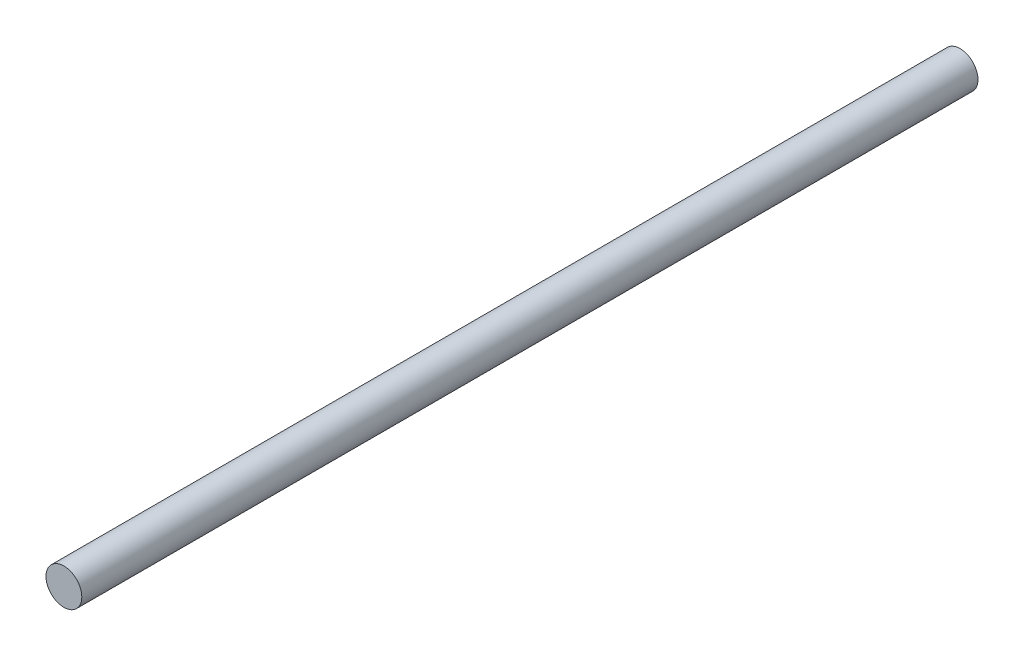
SolidWorks part; units mm, degrees
ref_plane "前视基准面" through (0, 0, 0) normal (0, 0, 1) x (1, 0, 0)
ref_plane "上视基准面" through (0, 0, 0) normal (0, 1, 0) x (1, 0, 0)
ref_plane "右视基准面" through (0, 0, 0) normal (1, 0, 0) x (0, 0, -1)
other "Configuration Table"
sketch "草图1" plane through (0, 0, 0) normal (0, 0, 1) x (1, 0, 0)
  circle A0 centre (0, 0) radius 4
  dimension "D1" = 8
extrude "凸台-拉伸1" add sketch "草图1" along normal blind 200 contours A0
